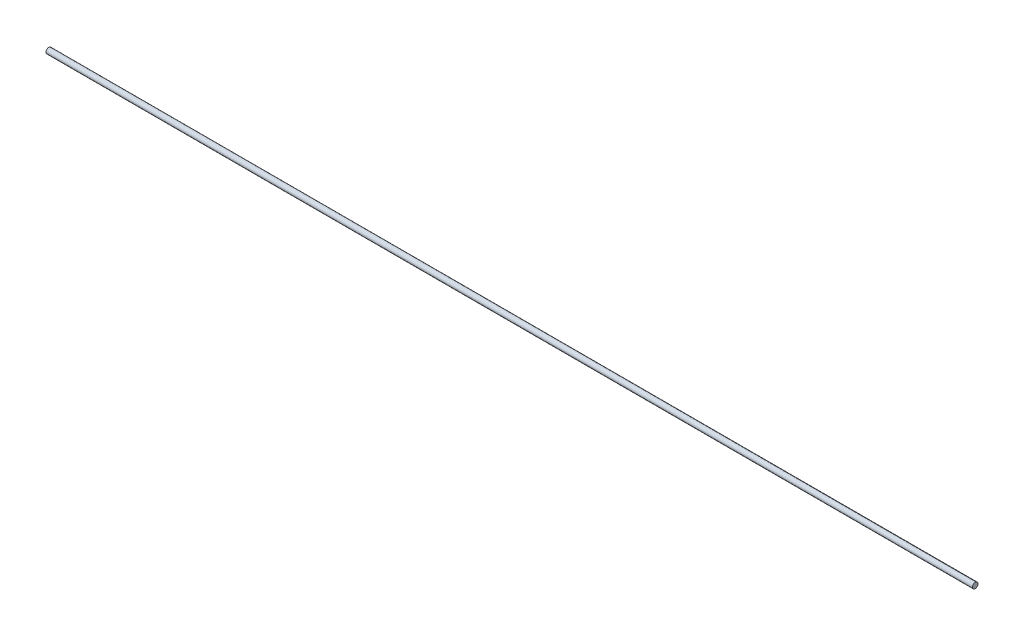
SolidWorks part; units mm, degrees
ref_plane "Спереди" through (0, 0, 0) normal (0, 0, 1) x (1, 0, 0)
ref_plane "Сверху" through (0, 0, 0) normal (0, 1, 0) x (1, 0, 0)
ref_plane "Справа" through (0, 0, 0) normal (1, 0, 0) x (0, 0, -1)
sketch "Эскиз1" plane through (0, 0, 0) normal (1, 0, 0) x (0, 0, -1)
  circle A0 centre (0, 0) radius 6
  dimension "D1" = 12
extrude "Бобышка-Вытянуть1" add sketch "Эскиз1" along normal blind 2000
